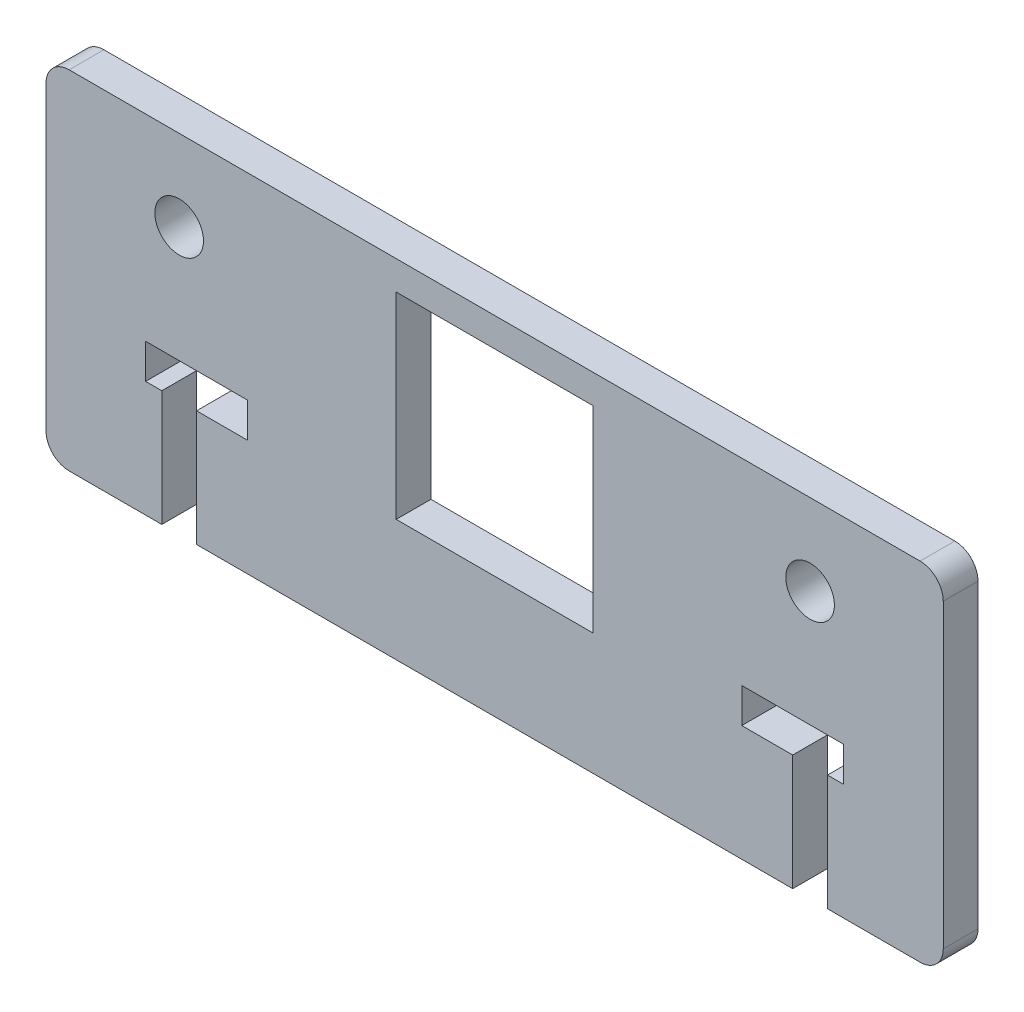
SolidWorks part; units mm, degrees
material "Zoltek Panex 33"
ref_plane "前视基准面" through (0, 0, 0) normal (0, 0, 1) x (1, 0, 0)
ref_plane "上视基准面" through (0, 0, 0) normal (0, 1, 0) x (1, 0, 0)
ref_plane "右视基准面" through (0, 0, 0) normal (1, 0, 0) x (0, 0, -1)
sketch "草图1" plane through (0, 0, 0) normal (0, 0, 1) x (1, 0, 0)
  line L2 (1.45, 41.9586) -> (27.19, 41.9586)
  line L5 (-0.05, 46.9586) -> (-0.05, 41.9586)
  line L6 (-0.05, 41.9586) -> (1.45, 41.9586) construction
  line L7 (-0.05, 41.9586) -> (-5.05, 41.9586)
  line L8 (-5.05, 41.9586) -> (-5.05, 56.9586)
  line L9 (-5.05, 56.9586) -> (14.32, 56.9586)
  line L10 (33.69, 56.9586) -> (33.69, 41.9586)
  line L11 (33.69, 41.9586) -> (28.69, 41.9586)
  line L14 (27.94, 53.4586) -> (0.7, 53.4586) construction
  line L15 (14.32, 53.4586) -> (14.32, 56.9586) construction
  line L19 (14.32, 56.9586) -> (33.69, 56.9586)
  line L20 (10.07, 47.2086) -> (18.57, 47.2086)
  line L31 (14.32, 41.9586) -> (14.32, 53.4586) construction
  line L33 (1.45, 41.9586) -> (1.45, 46.9586)
  line L34 (1.45, 46.9586) -> (3.65, 46.9586)
  line L35 (3.65, 46.9586) -> (3.65, 48.4586)
  line L36 (3.65, 48.4586) -> (-0.75, 48.4586)
  line L37 (-0.75, 48.4586) -> (-0.75, 46.9586)
  line L38 (-0.75, 46.9586) -> (-0.05, 46.9586)
  line L39 (0.7, 41.9586) -> (0.7, 56.9586) construction
  line L40 (27.19, 41.9586) -> (27.19, 46.9586)
  line L41 (28.69, 46.9586) -> (28.69, 41.9586)
  line L42 (29.39, 46.9586) -> (28.69, 46.9586)
  line L43 (29.39, 48.4586) -> (29.39, 46.9586)
  line L44 (24.99, 48.4586) -> (29.39, 48.4586)
  line L45 (24.99, 46.9586) -> (24.99, 48.4586)
  line L46 (27.19, 46.9586) -> (24.99, 46.9586)
  line L47 (10.07, 47.2086) -> (10.07, 55.7086)
  line L48 (10.07, 55.7086) -> (18.57, 55.7086)
  line L49 (18.57, 47.2086) -> (18.57, 55.7086)
  line L50 (10.07, 47.2086) -> (18.57, 55.7086) construction
  line L51 (10.07, 55.7086) -> (18.57, 47.2086) construction
  circle A0 centre (27.94, 53.4586) radius 1.05
  circle A1 centre (0.7, 53.4586) radius 1.05
  point P2 (14.32, 51.4586)
  dimension "D8" = 2.1
  dimension "D2" = 1.5
  dimension "D3" = 25.74
  dimension "D4" = 5
  dimension "D5" = 5
  dimension "D6" = 15
  dimension "D7" = 2.2
  dimension "D9" = 8.5
  dimension "D10" = 8.5
  dimension "D11" = 3.5
  dimension "D12" = 2.2
  dimension "D13" = 1.5
  dimension "D14" = 5
  dimension "D15" = 9.5
extrude "凸台-拉伸1" add sketch "草图1" along normal blind 1.5
fillet "圆角1" radius 1 4 edges at (33.69, 41.9586, 0.75) (33.69, 56.9586, 0.75) (-5.05, 41.9586, 0.75) (-5.05, 56.9586, 0.75)
